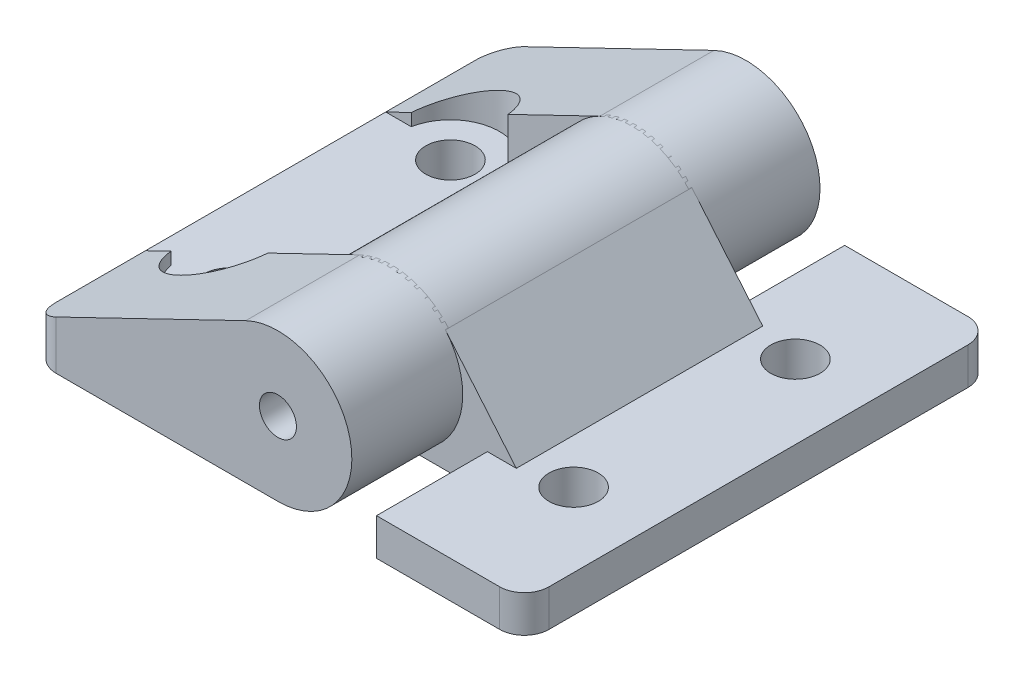
SolidWorks part; units mm, degrees
ref_plane "前视基准面" through (0, 0, 0) normal (0, 0, 1) x (1, 0, 0)
ref_plane "上视基准面" through (0, 0, 0) normal (0, 1, 0) x (1, 0, 0)
ref_plane "右视基准面" through (0, 0, 0) normal (1, 0, 0) x (0, 0, -1)
other "Configuration Table"
sketch "草图1" plane through (0, 0, 0) normal (0, 0, 1) x (1, 0, 0)
  line L0 (0, -6) -> (20, -6)
  line L1 (10.3497, -3) -> (20, -3)
  line L2 (10.3497, -3) -> (4.5963, 3.8567)
  line L3 (20, -3) -> (20, -6)
  arc A0 (4.5963, 3.8567) -> (0, -6) centre (0, 0) ccw
  circle A1 centre (0, 0) radius 1.5
  dimension "D1" = 12
  dimension "D5" = 3
  dimension "D2" = 20
  dimension "D3" = 3
  dimension "D4" = 130
extrude "凸台-拉伸1" add sketch "草图1" along normal mid plane 20
sketch "草图2" plane through (0, -3, 0) normal (0, 1, 0) x (1, 0, 0)
  line L0 (20, -10) -> (20, 10) construction
  line L1 (8, 19) -> (20, 19)
  line L2 (8, 19) -> (8, -19)
  line L3 (8, -19) -> (20, -19)
  line L4 (20, 19) -> (20, -19)
  point P6 (20, 0)
  dimension "D1" = 38
  dimension "D2" = 12
extrude "凸台-拉伸2" add sketch "草图2" against normal blind 3
sketch "草图3" plane through (0, 0, 0) normal (0, 0, 1) x (1, 0, 0)
  line L0 (0, -6) -> (-20, -6)
  line L1 (-20, -6) -> (-20, -3)
  line L2 (-20, -3) -> (-2.6104, 5.4024)
  line L3 (20, -6) -> (20, -3) construction
  arc A0 (0, -6) -> (-2.6104, 5.4024) centre (0, 0) ccw
  circle A1 centre (0, 0) radius 1.5
  dimension "D1" = 12
  dimension "D4" = 3
  dimension "D2" = 3
  dimension "D3" = 40
extrude "凸台-拉伸3" add sketch "草图3" along normal mid plane 38 separate body
sketch "草图4" plane through (0, 0, 0) normal (0, 1, 0) x (1, 0, 0)
  line L5 (-6.5, 9.75) -> (6.5, 9.75)
  line L6 (-6.5, 9.75) -> (-6.5, -9.75)
  line L7 (-6.5, -9.75) -> (6.5, -9.75)
  line L8 (6.5, 9.75) -> (6.5, -9.75)
  line L9 (-6.5, 9.75) -> (6.5, -9.75) construction
  line L10 (-6.5, -9.75) -> (6.5, 9.75) construction
  point P0 (0, 0)
  dimension "D1" = 19.5
  dimension "D2" = 13
extrude "切除-拉伸1" cut sketch "草图4" against normal through all both and the other way through all
sketch "草图5" plane through (0, -6, 0) normal (0, -1, 0) x (1, 0, 0)
  line L0 (-20, 19) -> (-20, -19) construction
  line L1 (-33.5, 9.75) -> (-17.9291, 9.75)
  line L2 (-33.5, 9.75) -> (-33.5, -9.75)
  line L3 (-33.5, -9.75) -> (-17.9291, -9.75)
  line L4 (-6.5, 9.75) -> (-6.5, -9.75)
  line L5 (-33.5, 9.75) -> (-6.5, -9.75) construction
  line L6 (-33.5, -9.75) -> (-6.5, 9.75) construction
  line L7 (0, 0) -> (-12.7722, 0) construction
  line L8 (-10.0709, 9.75) -> (-6.5, 9.75)
  line L9 (-10.0709, -9.75) -> (-6.5, -9.75)
  arc A0 (-10.0709, 9.75) -> (-17.9291, 9.75) centre (-14, 9) ccw
  arc A1 (-10.0709, -9.75) -> (-17.9291, -9.75) centre (-14, -9) cw
  point P0 (-20, 0)
  dimension "D1" = 18
  dimension "D3" = 8
  dimension "D2" = 14
extrude "切除-拉伸2" cut sketch "草图5" against normal through all from offset 3 offset against normal yes
sketch "草图6" plane through (0, -3, 0) normal (0, 1, 0) x (1, 0, 0)
  circle A0 centre (-14, 9) radius 2
  circle A1 centre (-14, -9) radius 2
  dimension "D1" = 4
  dimension "D2" = 4
extrude "切除-拉伸3" cut sketch "草图6" against normal through all
sketch "草图7" plane through (0, -3, 0) normal (0, 1, 0) x (1, 0, 0)
  line L0 (0, 0) -> (32.6442, 0) construction
  circle A0 centre (14, 9) radius 2
  circle A1 centre (14, -9) radius 2
  dimension "D1" = 18
  dimension "D3" = 4
  dimension "D2" = 14
extrude "切除-拉伸4" cut sketch "草图7" against normal through all
fillet "圆角1" radius 2 2 edges at (-20, -4.5, -19) (-20, -4.5, 19)
fillet "圆角2" radius 2 2 edges at (20, -4.5, 19) (20, -4.5, -19)
